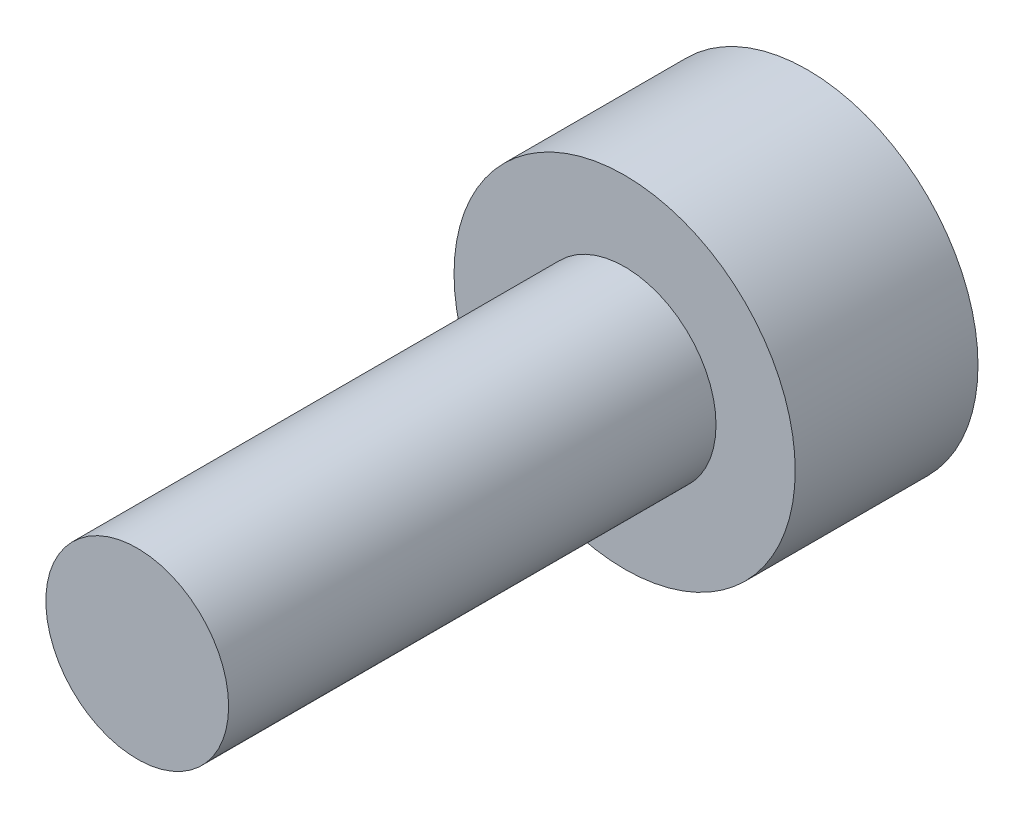
SolidWorks part; units mm, degrees
ref_plane "Front Plane" through (0, 0, 0) normal (0, 0, 1) x (1, 0, 0)
ref_plane "Top Plane" through (0, 0, 0) normal (0, 1, 0) x (1, 0, 0)
ref_plane "Right Plane" through (0, 0, 0) normal (1, 0, 0) x (0, 0, -1)
sketch "Sketch1" plane through (0, 0, 0) normal (0, 0, 1) x (1, 0, 0)
  circle A0 centre (0, 0) radius 2.8
extrude "Head" add sketch "Sketch1" along normal blind 3 from offset 3
sketch "Sketch2" plane through (0, 0, 0) normal (0, 0, 1) x (1, 0, 0)
  circle A0 centre (0, 0) radius 1.5
extrude "Shank" add sketch "Sketch2" along normal blind 8
sketch "Sketch3" plane through (0, 0, 0) normal (0, 0, 1) x (1, 0, 0)
  line L0 (1.25, 0.7217) -> (0, 1.4434)
  line L1 (0, 1.4434) -> (-1.25, 0.7217)
  line L2 (-1.25, 0.7217) -> (-1.25, -0.7217)
  line L3 (-1.25, -0.7217) -> (0, -1.4434)
  line L4 (0, -1.4434) -> (1.25, -0.7217)
  line L5 (1.25, -0.7217) -> (1.25, 0.7217)
extrude "Hex socket" cut sketch "Sketch3" along normal blind 1.8 from offset 3.2
